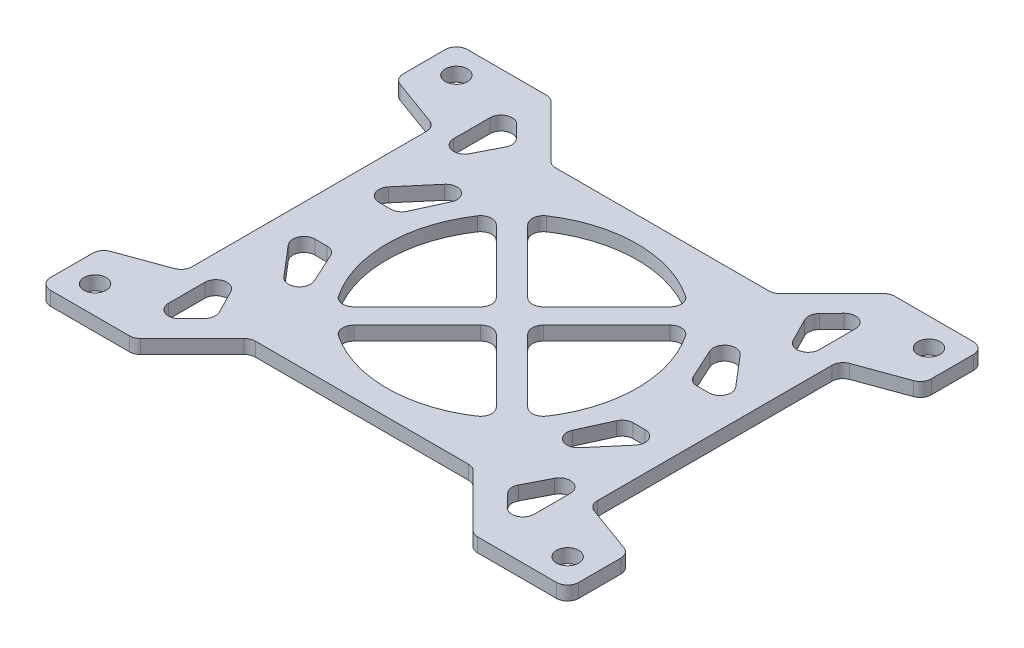
SolidWorks part; units mm, degrees
material "ABS"
ref_plane "前视基准面" through (0, 0, 0) normal (0, 0, 1) x (1, 0, 0)
ref_plane "上视基准面" through (0, 0, 0) normal (0, 1, 0) x (1, 0, 0)
ref_plane "右视基准面" through (0, 0, 0) normal (1, 0, 0) x (0, 0, -1)
sketch "草图2" plane through (0, 0, 0) normal (0, 1, 0) x (1, 0, 0)
  line L1 (-47.5, 37.5) -> (-30.5, 37.5)
  line L2 (-47.5, 37.5) -> (-47.5, 26.5219)
  line L3 (-47.5, -37.5) -> (-30.5, -37.5)
  line L4 (47.5, 37.5) -> (47.5, 26.5219)
  line L5 (-47.5, 37.5) -> (47.5, -37.5) construction
  line L6 (-47.5, -37.5) -> (47.5, 37.5) construction
  line L7 (-36.45, 27) -> (36.45, 27) construction
  line L8 (-36.45, 27) -> (-36.45, -27) construction
  line L9 (-36.45, -27) -> (36.45, -27) construction
  line L10 (36.45, 27) -> (36.45, -27) construction
  line L11 (-36.45, 27) -> (36.45, -27) construction
  line L12 (-36.45, -27) -> (36.45, 27) construction
  line L13 (0, -27.5) -> (0, 27.5) construction
  line L19 (-37.5, 0) -> (37.5, 0) construction
  line L28 (-30.5, 37.5) -> (-20, 27)
  line L29 (-20, 27) -> (20, 27)
  line L30 (20, 27) -> (30.5, 37.5)
  line L31 (30.5, 37.5) -> (47.5, 37.5)
  line L32 (-47.5, 26.5219) -> (-36.45, 22.5)
  line L33 (-36.45, 22.5) -> (-36.45, -22.5)
  line L34 (-36.45, -22.5) -> (-47.5, -26.5219)
  line L35 (36.45, -22.5) -> (47.5, -26.5219)
  line L36 (36.45, 22.5) -> (36.45, -22.5)
  line L37 (47.5, 26.5219) -> (36.45, 22.5)
  line L38 (20, -27) -> (30.5, -37.5)
  line L39 (-20, -27) -> (20, -27)
  line L40 (-30.5, -37.5) -> (-20, -27)
  line L41 (-47.5, -26.5219) -> (-47.5, -37.5)
  line L42 (47.5, -26.5219) -> (47.5, -37.5)
  line L43 (30.5, -37.5) -> (47.5, -37.5)
  point P0 (0, 0)
  point P6 (0, 0)
  dimension "D1" = 75
  dimension "D2" = 95
  dimension "D3" = 54
  dimension "D4" = 72.9
  dimension "D13" = 40
  dimension "D14" = 45
  dimension "D15" = 110
extrude "凸台-拉伸1" add sketch "草图2" along normal blind 2.5
sketch "草图3" plane through (0, 2.5, 0) normal (0, 1, 0) x (1, 0, 0)
  line L0 (-42.5, 0) -> (0, 0) construction
  line L1 (-42.5, 32.5) -> (42.5, 32.5) construction
  line L2 (-42.5, 32.5) -> (-42.5, -32.5) construction
  line L3 (-42.5, -32.5) -> (42.5, -32.5) construction
  line L4 (42.5, 32.5) -> (42.5, -32.5) construction
  line L5 (-42.5, 32.5) -> (42.5, -32.5) construction
  line L6 (-42.5, -32.5) -> (42.5, 32.5) construction
  circle A0 centre (-42.5, -32.5) radius 2
  circle A1 centre (42.5, -32.5) radius 2
  circle A2 centre (42.5, 32.5) radius 2
  circle A3 centre (-42.5, 32.5) radius 2
  point P0 (0, 0)
  dimension "D1" = 4
  dimension "D2" = 65
  dimension "D3" = 85
extrude "切除-拉伸1" cut sketch "草图3" against normal through all
sketch "草图4" plane through (0, 2.5, 0) normal (0, 1, 0) x (1, 0, 0)
  line L0 (-36.45, 0) -> (36.45, 0) construction
  line L1 (-36.45, 22.5) -> (-36.45, -22.5) construction
  line L2 (36.45, -22.5) -> (36.45, 22.5) construction
  line L3 (0, 27) -> (0, -27) construction
  line L4 (20, 27) -> (-20, 27) construction
  line L5 (-20, -27) -> (20, -27) construction
  line L6 (0, 0) -> (15.9099, 15.9099) construction
  line L7 (14.4327, 17.2611) -> (0, 2.8284)
  line L8 (17.2611, 14.4327) -> (2.8284, 0)
  line L9 (17.2611, -14.4327) -> (2.8284, 0)
  line L10 (14.4327, -17.2611) -> (0, -2.8284)
  line L11 (-14.4327, 17.2611) -> (0, 2.8284)
  line L12 (-17.2611, 14.4327) -> (-2.8284, 0)
  line L13 (-14.4327, -17.2611) -> (0, -2.8284)
  line L14 (-17.2611, -14.4327) -> (-2.8284, 0)
  line L15 (-17.2611, 25.4026) -> (-34.0141, 5.7379)
  line L16 (-34.0141, 5.7379) -> (-26.2601, 5.7379)
  line L17 (-26.2601, 5.7379) -> (-17.2611, 25.4026)
  line L18 (-32.8768, 14.1122) -> (-26.2601, 27)
  line L19 (-26.2601, 27) -> (-32.8768, 33.859)
  line L20 (-32.8768, 33.859) -> (-32.8768, 14.1122)
  line L21 (26.2601, 27) -> (32.8768, 33.859)
  line L22 (32.8768, 14.1122) -> (26.2601, 27)
  line L23 (32.8768, 33.859) -> (32.8768, 14.1122)
  line L24 (34.0141, 5.7379) -> (26.2601, 5.7379)
  line L25 (17.2611, 25.4026) -> (34.0141, 5.7379)
  line L26 (26.2601, 5.7379) -> (17.2611, 25.4026)
  line L27 (32.8768, -14.1122) -> (26.2601, -27)
  line L28 (32.8768, -33.859) -> (32.8768, -14.1122)
  line L29 (26.2601, -27) -> (32.8768, -33.859)
  line L30 (17.2611, -25.4026) -> (34.0141, -5.7379)
  line L31 (26.2601, -5.7379) -> (17.2611, -25.4026)
  line L32 (34.0141, -5.7379) -> (26.2601, -5.7379)
  line L33 (-26.2601, -27) -> (-32.8768, -33.859)
  line L34 (-32.8768, -14.1122) -> (-26.2601, -27)
  line L35 (-32.8768, -33.859) -> (-32.8768, -14.1122)
  line L36 (-34.0141, -5.7379) -> (-26.2601, -5.7379)
  line L37 (-17.2611, -25.4026) -> (-34.0141, -5.7379)
  line L38 (-26.2601, -5.7379) -> (-17.2611, -25.4026)
  circle A0 centre (0, 0) radius 22.5 construction
  arc A1 (-14.4327, 17.2611) -> (14.4327, 17.2611) centre (0, 0) cw
  arc A2 (-17.2611, -14.4327) -> (-17.2611, 14.4327) centre (0, 0) cw
  arc A3 (14.4327, -17.2611) -> (-14.4327, -17.2611) centre (0, 0) cw
  arc A4 (17.2611, 14.4327) -> (17.2611, -14.4327) centre (0, 0) cw
  dimension "D1" = 45
  dimension "D2" = 45
  dimension "D3" = 2
extrude "切除-拉伸2" cut sketch "草图4" against normal through all
fillet "圆角1" radius 2 36 edges at (14.4327, 1.25, -17.2611) (0, 1.25, -2.8284) (26.2601, 1.25, 5.7379) (34.0141, 1.25, 5.7379) (17.2611, 1.25, 25.4026) (-26.2601, 1.25, 27) (-32.8768, 1.25, 33.859) (-32.8768, 1.25, 14.1122) (-34.0141, 1.25, 5.7379) (-26.2601, 1.25, 5.7379) (-17.2611, 1.25, 25.4026) (-26.2601, 1.25, -5.7379) (-34.0141, 1.25, -5.7379) (-17.2611, 1.25, -25.4026) (-17.2611, 1.25, -14.4327) (-2.8284, 1.25, 0) (-17.2611, 1.25, 14.4327) (17.2611, 1.25, 14.4327) (2.8284, 1.25, 0) (17.2611, 1.25, -14.4327) (-14.4327, 1.25, 17.2611) (0, 1.25, 2.8284) (14.4327, 1.25, 17.2611) (32.8768, 1.25, 33.859) (26.2601, 1.25, 27) (32.8768, 1.25, 14.1122) (34.0141, 1.25, -5.7379) (26.2601, 1.25, -5.7379) (17.2611, 1.25, -25.4026) (26.2601, 1.25, -27) (32.8768, 1.25, -33.859) (32.8768, 1.25, -14.1122) (-32.8768, 1.25, -33.859) (-26.2601, 1.25, -27) (-32.8768, 1.25, -14.1122) (-14.4327, 1.25, -17.2611)
fillet "圆角2" radius 2 20 edges at (30.5, 1.25, 37.5) (20, 1.25, 27) (-30.5, 1.25, 37.5) (-47.5, 1.25, 37.5) (-47.5, 1.25, 26.5219) (-36.45, 1.25, 22.5) (-36.45, 1.25, -22.5) (-47.5, 1.25, -26.5219) (-47.5, 1.25, -37.5) (-30.5, 1.25, -37.5) (-20, 1.25, -27) (20, 1.25, -27) (30.5, 1.25, -37.5) (47.5, 1.25, -37.5) (47.5, 1.25, -26.5219) (36.45, 1.25, -22.5) (36.45, 1.25, 22.5) (47.5, 1.25, 26.5219) (47.5, 1.25, 37.5) (-20, 1.25, 27)
